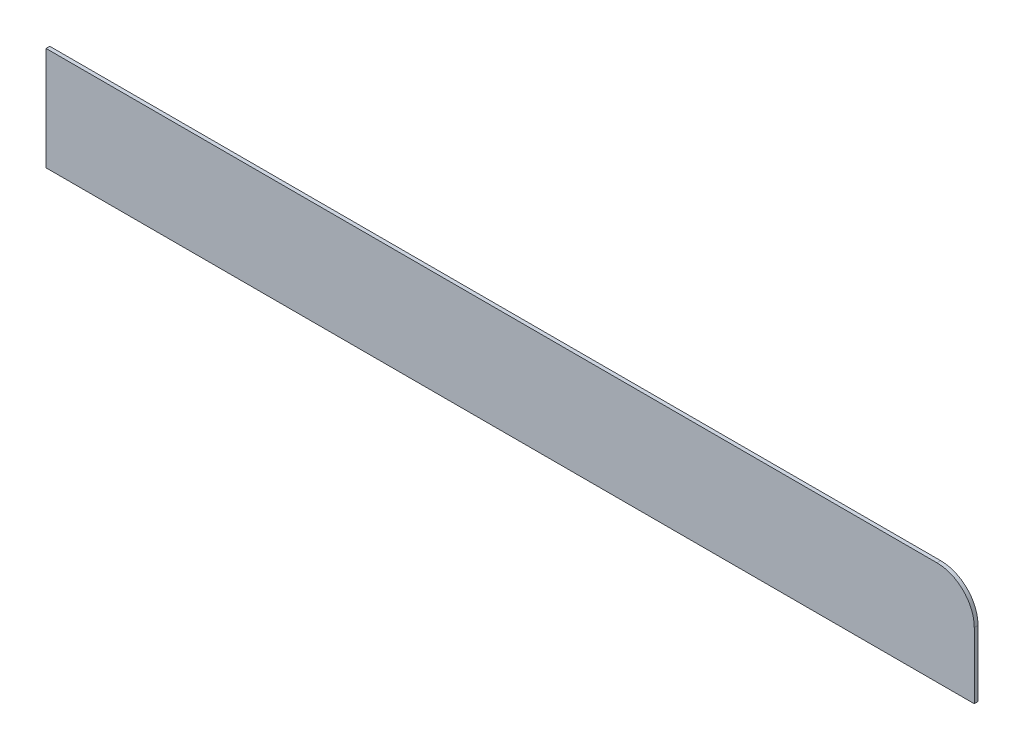
SolidWorks part; units mm, degrees
ref_plane "Front" through (0, 0, 0) normal (0, 0, 1) x (1, 0, 0)
ref_plane "Top" through (0, 0, 0) normal (0, 1, 0) x (1, 0, 0)
ref_plane "Right" through (0, 0, 0) normal (1, 0, 0) x (0, 0, -1)
sketch "Эскиз1" plane through (0, 0, 0) normal (0, 0, 1) x (1, 0, 0)
  line L0 (-3, 40) -> (-3, -43)
  line L1 (-3, 40) -> (711.9923, 40)
  line L2 (-3, -43) -> (741.9923, -43)
  line L3 (741.9923, 10) -> (741.9923, -43)
  arc A0 (711.9923, 40) -> (741.9923, 10) centre (711.9923, 10) cw
  dimension "D1" = 30
extrude "Бобышка-Вытянуть1" add sketch "Эскиз1" along normal blind 3
